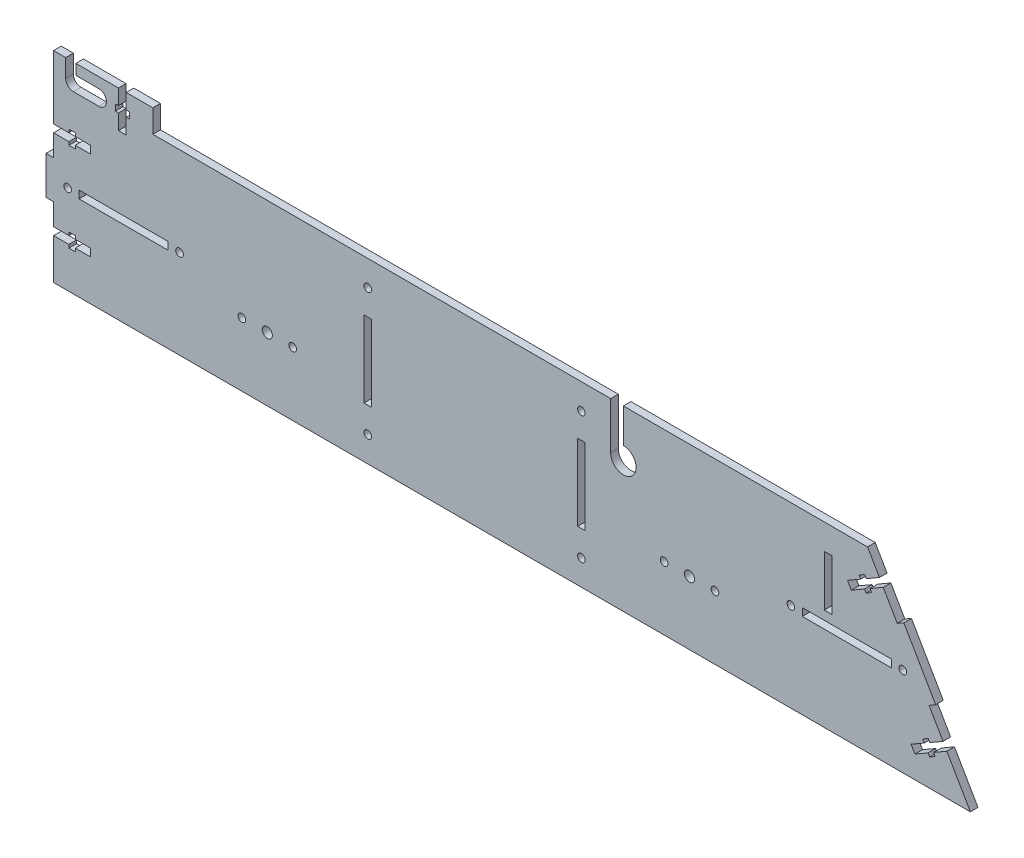
SolidWorks part; units mm, degrees
ref_plane "Спереди" through (0, 0, 0) normal (0, 0, 1) x (1, 0, 0)
ref_plane "Сверху" through (0, 0, 0) normal (0, 1, 0) x (1, 0, 0)
ref_plane "Справа" through (0, 0, 0) normal (1, 0, 0) x (0, 0, -1)
sketch "Эскиз1" plane through (0, 0, 0) normal (0, 0, 1) x (1, 0, 0)
  line L0 (320, 70) -> (360.4145, 0)
  line L2 (0, 0) -> (0, 70)
  line L3 (0, 70) -> (320, 70)
  line L5 (0, 0) -> (360.4145, 0)
  circle A0 centre (84, 25) radius 2
  circle A1 centre (250, 25) radius 2
  circle A2 centre (84, 25) radius 10 construction
  circle A3 centre (94, 25) radius 1.5
  circle A4 centre (74, 25) radius 1.5
  circle A5 centre (240, 25) radius 1.5
  circle A6 centre (260, 25) radius 1.5
  circle A7 centre (250, 25) radius 10 construction
  dimension "D4" = 4
  dimension "D8" = 20
  dimension "D9" = 3
  dimension "D10" = 80.829
  dimension "D1" = 320
  dimension "D2" = 70
  dimension "D3" = 60
  dimension "D5" = 25
  dimension "D6" = 166
  dimension "D7" = 84
extrude "Бобышка-Вытянуть1" add sketch "Эскиз1" along normal blind 3
sketch "Эскиз2" plane through (0, 70, 0) normal (0, 1, 0) x (1, 0, 0)
  line L0 (320, -3) -> (0, -3) construction
  line L1 (301, -3) -> (282, -3)
  line L2 (301, -3) -> (301, 0)
  line L3 (301, 0) -> (282, 0)
  line L4 (282, -3) -> (282, 0)
  line L5 (320, 0) -> (0, 0) construction
  dimension "D1" = 19
  dimension "D2" = 19
extrude "Бобышка-Вытянуть2" add sketch "Эскиз2" along normal blind 3
pattern_linear "Линейный массив1" count 9 spacing 28 along (-1, 0, 0) of "Бобышка-Вытянуть2"
sketch "Эскиз3" plane through (0, 0, 3) normal (0, 0, 1) x (1, 0, 0)
  line L0 (198, 73) -> (217, 73) construction
  line L1 (206, 50) -> (209, 50)
  line L2 (206, 50) -> (206, 20)
  line L3 (206, 20) -> (209, 20)
  line L4 (209, 50) -> (209, 20)
  line L5 (206, 50) -> (209, 20) construction
  line L6 (206, 20) -> (209, 50) construction
  line L7 (0, 70) -> (0, 0) construction
  line L8 (114, 73) -> (133, 73) construction
  line L9 (122, 50) -> (125, 50)
  line L10 (122, 50) -> (122, 20)
  line L11 (122, 20) -> (125, 20)
  line L12 (125, 50) -> (125, 20)
  line L13 (122, 50) -> (125, 20) construction
  line L14 (122, 20) -> (125, 50) construction
  point P0 (207.5, 35)
  point P9 (207.5, 73)
  point P10 (123.5, 73)
  point P13 (0, 35)
  point P14 (123.5, 35)
  point P19 (123.5, 20)
  point P21 (207.5, 20)
  dimension "D3" = 123.5
  dimension "D1" = 30
  dimension "D2" = 3
  dimension "D4" = 84
extrude "Вырез-Вытянуть1" cut sketch "Эскиз3" against normal blind 3
sketch "Эскиз4" plane through (0, 0, 3) normal (0, 0, 1) x (1, 0, 0)
  line L0 (0, 70) -> (0, 0) construction
  line L1 (294.3412, 36.5) -> (329.3412, 36.5)
  line L2 (294.3412, 36.5) -> (294.3412, 33.5)
  line L3 (294.3412, 33.5) -> (329.3412, 33.5)
  line L4 (329.3412, 36.5) -> (329.3412, 33.5)
  line L5 (294.3412, 36.5) -> (329.3412, 33.5) construction
  line L6 (294.3412, 33.5) -> (329.3412, 36.5) construction
  line L7 (10, 36.5) -> (45, 36.5)
  line L8 (10, 36.5) -> (10, 33.5)
  line L9 (10, 33.5) -> (45, 33.5)
  line L10 (45, 36.5) -> (45, 33.5)
  line L11 (10, 36.5) -> (45, 33.5) construction
  line L12 (10, 33.5) -> (45, 36.5) construction
  line L14 (329.3412, 36.5) -> (339.3412, 36.5) construction
  line L15 (360.4145, 0) -> (320, 70) construction
  circle A0 centre (84, 25) radius 35 construction
  point P0 (311.8412, 35)
  point P5 (27.5, 35)
  point P15 (0, 35)
  point P18 (340.2073, 35)
  dimension "D5" = 70
  dimension "D1" = 35
  dimension "D2" = 3
  dimension "D3" = 10
  dimension "D4" = 10
  dimension "D6" = 40.4145
  dimension "D7" = 284.3412
extrude "Вырез-Вытянуть2" cut sketch "Эскиз4" against normal blind 3
sketch "Эскиз5" plane through (0, 0, 3) normal (0, 0, 1) x (1, 0, 0)
  line L0 (125, 50) -> (122, 50) construction
  line L1 (209, 50) -> (206, 50) construction
  line L2 (294.3412, 36.5) -> (294.3412, 33.5) construction
  line L3 (10, 36.5) -> (10, 33.5) construction
  circle A0 centre (5.5, 35) radius 1.5
  circle A1 centre (49.5, 35) radius 1.5
  circle A2 centre (123.5, 60) radius 1.5
  circle A3 centre (123.5, 10) radius 1.5
  circle A4 centre (207.5, 60) radius 1.5
  circle A5 centre (207.5, 10) radius 1.5
  circle A6 centre (289.8412, 35) radius 1.5
  circle A7 centre (333.8412, 35) radius 1.5
  point P20 (123.5, 50)
  point P29 (207.5, 50)
  point P34 (294.3412, 35)
  point P42 (10, 35)
  dimension "D1" = 3
  dimension "D2" = 10
  dimension "D3" = 10
  dimension "D4" = 4.5
  dimension "D5" = 4.5
  dimension "D6" = 4.5
  dimension "D7" = 4.5
extrude "Вырез-Вытянуть3" cut sketch "Эскиз5" against normal blind 3
sketch "Эскиз6" plane through (0, 0, 3) normal (0, 0, 1) x (1, 0, 0)
  line L0 (0, 54) -> (6, 54)
  line L1 (6, 54) -> (6, 55.25)
  line L2 (6, 55.25) -> (8.5, 55.25)
  line L3 (8.5, 55.25) -> (8.5, 54)
  line L4 (8.5, 54) -> (14.5, 54)
  line L5 (14.5, 54) -> (14.5, 51)
  line L6 (14.5, 51) -> (8.5, 51)
  line L7 (8.5, 51) -> (8.5, 49.75)
  line L8 (8.5, 49.75) -> (6, 49.75)
  line L9 (6, 49.75) -> (6, 51)
  line L10 (6, 51) -> (0, 51)
  line L13 (0, 19) -> (6, 19)
  line L14 (6, 19) -> (6, 20.25)
  line L15 (6, 20.25) -> (8.5, 20.25)
  line L16 (8.5, 20.25) -> (8.5, 19)
  line L17 (8.5, 19) -> (14.5, 19)
  line L18 (14.5, 19) -> (14.5, 16)
  line L19 (14.5, 16) -> (8.5, 16)
  line L20 (8.5, 16) -> (8.5, 14.75)
  line L21 (8.5, 14.75) -> (6, 14.75)
  line L22 (6, 14.75) -> (6, 16)
  line L23 (6, 16) -> (0, 16)
  line L24 (0, 70) -> (0, 0) construction
  line L25 (0, 0) -> (360.4145, 0) construction
  line L26 (0, 54) -> (0, 51)
  line L27 (0, 19) -> (0, 16)
  point P12 (7.25, 49.75)
  point P28 (7.25, 14.75)
  point P31 (14.5, 52.5)
  point P32 (14.5, 17.5)
  dimension "D1" = 2.5
  dimension "D2" = 3
  dimension "D3" = 5.5
  dimension "D4" = 6
  dimension "D5" = 6
  dimension "D6" = 2.5
  dimension "D7" = 3
  dimension "D8" = 5.5
  dimension "D9" = 6
  dimension "D10" = 6
  dimension "D11" = 35
  dimension "D12" = 17.5
extrude "Вырез-Вытянуть4" cut sketch "Эскиз6" against normal blind 3
sketch "Эскиз7" plane through (0, 0, 3) normal (0, 0, 1) x (1, 0, 0)
  line L0 (324.6645, 61.9208) -> (319.4684, 58.9208)
  line L1 (319.4684, 58.9208) -> (318.8434, 60.0033)
  line L2 (318.8434, 60.0033) -> (316.6783, 58.7533)
  line L3 (316.6783, 58.7533) -> (317.3033, 57.6708)
  line L4 (317.3033, 57.6708) -> (312.1072, 54.6708)
  line L5 (312.1072, 54.6708) -> (313.6072, 52.0727)
  line L6 (313.6072, 52.0727) -> (318.8033, 55.0727)
  line L7 (318.8033, 55.0727) -> (319.4283, 53.9902)
  line L8 (319.4283, 53.9902) -> (321.5934, 55.2402)
  line L9 (321.5934, 55.2402) -> (320.9684, 56.3227)
  line L10 (320.9684, 56.3227) -> (326.1645, 59.3227)
  line L11 (326.1645, 59.3227) -> (324.6645, 61.9208)
  line L12 (349.6645, 18.6195) -> (344.4684, 15.6195)
  line L13 (344.4684, 15.6195) -> (343.8434, 16.7021)
  line L14 (343.8434, 16.7021) -> (341.6783, 15.4521)
  line L15 (341.6783, 15.4521) -> (342.3033, 14.3695)
  line L16 (342.3033, 14.3695) -> (337.1072, 11.3695)
  line L17 (337.1072, 11.3695) -> (338.6072, 8.7715)
  line L18 (338.6072, 8.7715) -> (343.8033, 11.7715)
  line L19 (343.8033, 11.7715) -> (344.4283, 10.6889)
  line L20 (344.4283, 10.6889) -> (346.5934, 11.9389)
  line L21 (346.5934, 11.9389) -> (345.9684, 13.0215)
  line L22 (345.9684, 13.0215) -> (351.1645, 16.0215)
  line L23 (351.1645, 16.0215) -> (349.6645, 18.6195)
  line L24 (360.4145, 0) -> (320, 70) construction
  point P24 (350.4145, 17.3205)
  dimension "D1" = 6
  dimension "D2" = 2.5
  dimension "D3" = 3
  dimension "D4" = 5.5
  dimension "D5" = 6
  dimension "D6" = 2.5
  dimension "D7" = 3
  dimension "D8" = 5.5
  dimension "D9" = 50
  dimension "D10" = 20
extrude "Вырез-Вытянуть5" cut sketch "Эскиз7" against normal blind 3
sketch "Эскиз8" plane through (0, 70, 0) normal (0, 1, 0) x (1, 0, 0)
  line L0 (58, -3) -> (0, -3) construction
  line L1 (0, 0) -> (39, 0)
  line L2 (0, 0) -> (0, -3)
  line L3 (0, -3) -> (39, -3)
  line L4 (39, 0) -> (39, -3)
  dimension "D1" = 39
extrude "Бобышка-Вытянуть3" add sketch "Эскиз8" along normal blind 9
sketch "Эскиз11" plane through (270.3109, 156.0641, 0) normal (0.866, 0.5, 0) x (0, 0, -1)
  line L0 (-3, -158.7073) -> (-3, -111.7073) construction
  line L1 (-3, -147.7073) -> (0, -147.7073)
  line L2 (-3, -147.7073) -> (-3, -122.7073)
  line L3 (-3, -122.7073) -> (0, -122.7073)
  line L4 (0, -147.7073) -> (0, -122.7073)
  line L5 (0, -158.7073) -> (0, -111.7073) construction
  point P9 (-3, -135.2073)
  point P10 (-3, -135.2073)
  dimension "D1" = 25
extrude "Бобышка-Вытянуть5" add sketch "Эскиз11" along normal blind 3
sketch "Эскиз12" plane through (0, 0, 0) normal (-1, 0, 0) x (0, 0, 1)
  line L0 (0, 51) -> (0, 19) construction
  line L1 (0, 27.5) -> (3, 27.5)
  line L2 (0, 27.5) -> (0, 42.5)
  line L3 (0, 42.5) -> (3, 42.5)
  line L4 (3, 27.5) -> (3, 42.5)
  line L5 (3, 51) -> (3, 19) construction
  point P9 (0, 35)
  point P10 (0, 35)
  dimension "D1" = 15
extrude "Бобышка-Вытянуть6" add sketch "Эскиз12" along normal blind 3
sketch "Эскиз13" plane through (0, 0, 3) normal (0, 0, 1) x (1, 0, 0)
  line L1 (58, 70) -> (301, 70)
  line L2 (58, 70) -> (58, 73)
  line L3 (58, 73) -> (301, 73)
  line L4 (301, 70) -> (301, 73)
extrude "Вырез-Вытянуть7" cut sketch "Эскиз13" against normal blind 3
sketch "Эскиз14" plane through (0, 0, 3) normal (0, 0, 1) x (1, 0, 0)
  line L0 (0, 0) -> (360.4145, 0) construction
  line L6 (306, 60) -> (303, 60)
  line L7 (306, 60) -> (306, 40)
  line L8 (306, 40) -> (303, 40)
  line L9 (303, 60) -> (303, 40)
  dimension "D1" = 306
  dimension "D2" = 40
  dimension "D5" = 3
  dimension "D7" = 20
extrude "Вырез-Вытянуть8" cut sketch "Эскиз14" against normal blind 10
sketch "Эскиз15" plane through (0, 0, 3) normal (0, 0, 1) x (1, 0, 0)
  line L0 (25.5, 79) -> (25.5, 73)
  line L1 (25.5, 73) -> (24.25, 73)
  line L2 (24.25, 73) -> (24.25, 70.5)
  line L3 (24.25, 70.5) -> (25.5, 70.5)
  line L4 (25.5, 70.5) -> (25.5, 64.5)
  line L5 (25.5, 64.5) -> (28.5, 64.5)
  line L6 (28.5, 64.5) -> (28.5, 70.5)
  line L7 (28.5, 70.5) -> (29.75, 70.5)
  line L8 (29.75, 70.5) -> (29.75, 73)
  line L9 (29.75, 73) -> (28.5, 73)
  line L10 (28.5, 73) -> (28.5, 79)
  line L11 (28.5, 79) -> (25.5, 79)
  line L12 (0, 79) -> (39, 79) construction
  point P15 (27, 79)
  dimension "D1" = 6
  dimension "D2" = 3
  dimension "D3" = 5.5
  dimension "D4" = 2.5
  dimension "D5" = 30
extrude "Вырез-Вытянуть9" cut sketch "Эскиз15" against normal blind 3
sketch "Эскиз16" plane through (0, 0, 3) normal (0, 0, 1) x (1, 0, 0)
  line L0 (7.75, 71.8989) -> (17.75, 71.8989) construction
  line L1 (8.75, 74.8989) -> (17.75, 74.8989)
  line L2 (7.75, 68.8989) -> (17.75, 68.8989)
  line L3 (0, 79) -> (25.5, 79) construction
  line L6 (4.75, 71.8989) -> (4.75, 79)
  line L7 (4.75, 79) -> (8.75, 79)
  line L8 (8.75, 74.8989) -> (8.75, 79)
  arc A0 (4.75, 71.8989) -> (7.75, 68.8989) centre (7.75, 71.8989) ccw
  arc A1 (17.75, 68.8989) -> (17.75, 74.8989) centre (17.75, 71.8989) ccw
  point P2 (12.75, 71.8989)
  point P10 (12.75, 79)
  dimension "D2" = 3
  dimension "D1" = 10
  dimension "D3" = 4
extrude "Вырез-Вытянуть10" cut sketch "Эскиз16" against normal blind 10
sketch "Эскиз17" plane through (0, 0, 3) normal (0, 0, 1) x (1, 0, 0)
  line L0 (320, 70) -> (39, 70) construction
  line L2 (219, 51.5) -> (219, 70)
  line L3 (219, 70) -> (224, 70)
  line L4 (224, 56.5) -> (224, 70)
  arc A0 (219, 51.5) -> (224, 56.5) centre (224, 51.5) ccw
  dimension "D1" = 10
  dimension "D2" = 15
  dimension "D3" = 15
  dimension "D4" = 5
extrude "Вырез-Вытянуть11" cut sketch "Эскиз17" against normal blind 10
